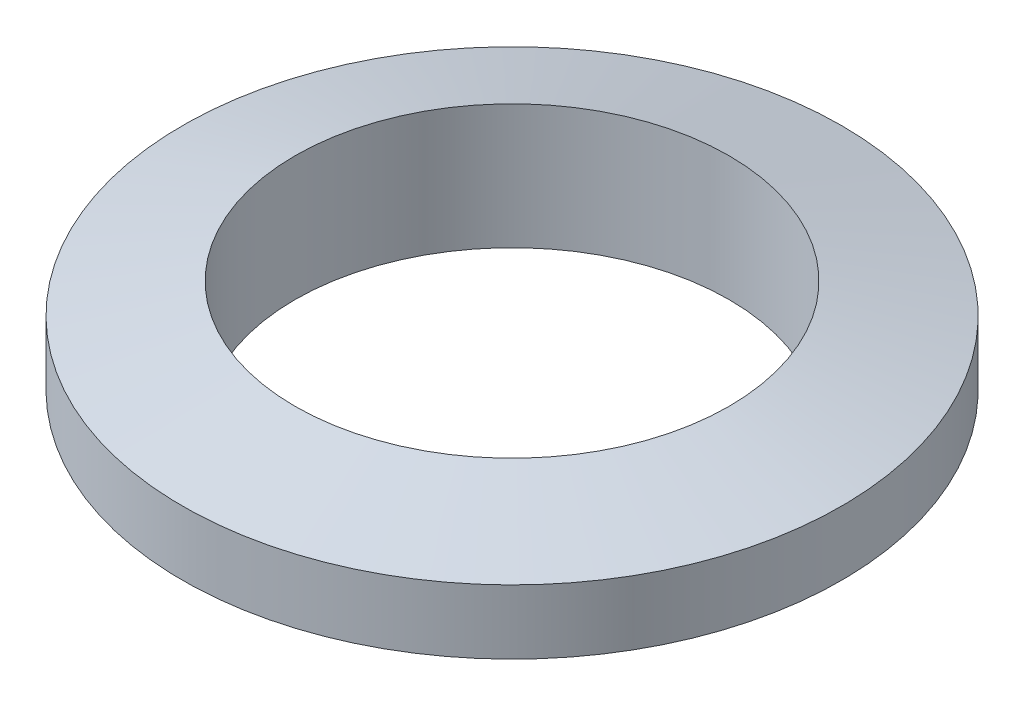
SolidWorks part; units mm, degrees
ref_plane "前视基准面" through (0, 0, 0) normal (0, 0, 1) x (1, 0, 0)
ref_plane "上视基准面" through (0, 0, 0) normal (0, 1, 0) x (1, 0, 0)
ref_plane "右视基准面" through (0, 0, 0) normal (1, 0, 0) x (0, 0, -1)
sketch "草图1" plane through (0, 0, 0) normal (0, 0, 1) x (1, 0, 0)
  line L0 (0, 0) -> (0, 64.6925) construction
  line L1 (0, -50.822) -> (0, 50.822) construction
  line L2 (-20.5, -2) -> (-20.5, 2)
  line L3 (27.6294, 0) -> (-27.6294, 0) construction
  line L4 (-20.5, 2) -> (-13.5, 3.8756)
  line L5 (-13.5, 3.8756) -> (-13.5, -3.8756)
  line L6 (0, 0) -> (29.7352, 0) construction
  line L7 (-20.5, -2) -> (-13.5, -3.8756)
  point P11 (13.5, -27.7112)
  point P13 (-20.5, 0)
  point P14 (-13.5, 0)
  dimension "D1" = 30
  dimension "D2" = 41
  dimension "D3" = 27
  dimension "D4" = 4
revolve "旋转1" add sketch "草图1" angle 360 about L0
